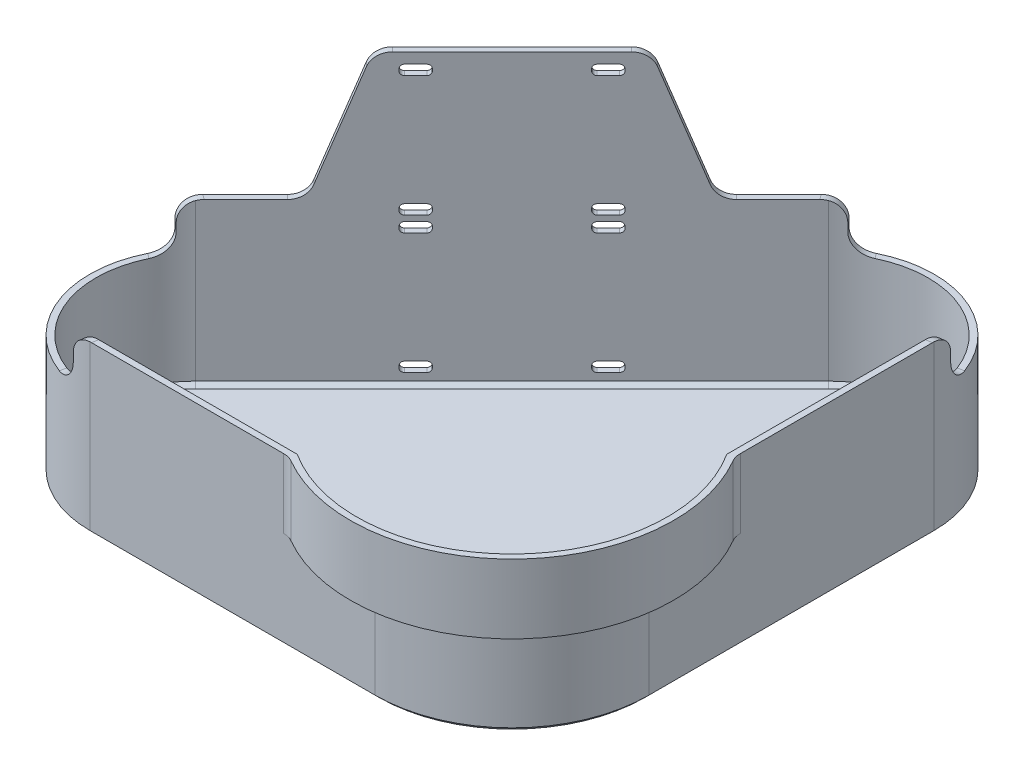
SolidWorks part; units mm, degrees
material "Nylon 101"
ref_plane "Front Plane" through (0, 0, 0) normal (0, 0, 1) x (1, 0, 0)
ref_plane "Top Plane" through (0, 0, 0) normal (0, 1, 0) x (1, 0, 0)
ref_plane "Right Plane" through (0, 0, 0) normal (1, 0, 0) x (0, 0, -1)
sketch "Module Geo" plane through (0, 0, 0) normal (0, 1, 0) x (1, 0, 0)
  line L0 (0, 0) -> (-208.4683, 0)
  line L1 (0, 208.4683) -> (-208.4683, 0)
  line L3 (0, 0) -> (0, 208.4683)
  arc A0 (-41.275, 0) -> (0, 41.275) centre (-41.275, 41.275) ccw
  arc A1 (-155.3516, 53.1166) -> (-133.35, 0) centre (-133.35, 31.115) ccw
  arc A2 (-53.1166, 155.3516) -> (0, 133.35) centre (-31.115, 133.35) cw
  circle A3 centre (-41.275, 41.275) radius 49.2125
  point P13 (0, 0)
  dimension "D1" = 31.115
  dimension "D2" = 41.275
  dimension "D4" = 98.425
  dimension "D3" = 92.075
ref_plane "Plane2" through (0, 0, 0) normal (0.7071, 0, -0.7071) x (-0.7071, 0, -0.7071)
sketch "Base Extrude" plane through (0, 0, 0) normal (0, 1, 0) x (1, 0, 0)
  line L0 (-55.5705, 30.7146) -> (-30.7146, 55.5705) construction
  line L1 (-30.7146, 55.5705) -> (-30.7146, 30.7146) construction
  line L2 (-30.7146, 30.7146) -> (-55.5705, 30.7146) construction
  line L12 (3, -3) -> (3, 215.7109)
  line L13 (3, 215.7109) -> (-215.7109, -3)
  line L14 (-215.7109, -3) -> (3, -3)
  line L15 (3, 41.275) -> (3, 133.35)
  line L16 (-55.2379, 157.4729) -> (-157.4729, 55.2379)
  line L17 (-133.35, -3) -> (-41.275, -3)
  circle A0 centre (-55.5705, 30.7146) radius 2.1526
  circle A1 centre (-30.7146, 30.7146) radius 2.1527
  circle A2 centre (-30.7146, 55.5705) radius 2.1527
  arc A14 (-157.4729, 55.2379) -> (-133.35, -3) centre (-133.35, 31.115) ccw
  arc A15 (-55.2379, 157.4729) -> (3, 133.35) centre (-31.115, 133.35) cw
  arc A16 (-41.275, -3) -> (3, 41.275) centre (-41.275, 41.275) ccw
  dimension "D2" = 4.3053
  dimension "D3" = 24.8559
  dimension "D4" = 10.5604
  dimension "D5" = 10.5604
  dimension "D1" = 3
extrude "Boss-Extrude1" add sketch "Base Extrude" along normal blind 2
sketch "Sketch3" plane through (0, 2, 0) normal (0, 1, 0) x (1, 0, 0)
  line L3 (-133.35, -3) -> (-41.275, -3)
  line L4 (3, 41.275) -> (3, 133.35)
  line L5 (-55.2379, 157.4729) -> (-157.4729, 55.2379)
  line L6 (-133.35, -3) -> (-41.275, -3)
  line L7 (3, 41.275) -> (3, 133.35)
  line L8 (-55.2379, 157.4729) -> (-157.4729, 55.2379)
  arc A3 (-157.4729, 55.2379) -> (-133.35, -3) centre (-133.35, 31.115) ccw
  arc A4 (-41.275, -3) -> (3, 41.275) centre (-41.275, 41.275) ccw
  arc A5 (3, 133.35) -> (-55.2379, 157.4729) centre (-31.115, 133.35) ccw
  arc A6 (-157.4729, 55.2379) -> (-133.35, -3) centre (-133.35, 31.115) ccw
  arc A7 (-41.275, -3) -> (3, 41.275) centre (-41.275, 41.275) ccw
  arc A8 (3, 133.35) -> (-55.2379, 157.4729) centre (-31.115, 133.35) ccw
  dimension "D1" = 0
extrude "Extrude-Thin1" add sketch "Sketch3" along normal blind 31.75 thin thin type one direction reverse wall 2
sketch "Sketch4" plane through (0, 33.75, 0) normal (0, 1, 0) x (1, 0, 0)
  line L0 (-133.35, -3) -> (-41.275, -3) construction
  line L1 (3, 41.275) -> (3, 133.35) construction
  line L5 (-133.35, -3) -> (-41.275, -3)
  line L6 (3, 41.275) -> (3, 133.35)
  line L7 (-55.2379, 157.4729) -> (-157.4729, 55.2379)
  line L8 (-133.35, -3) -> (-41.275, -3)
  line L9 (3, 41.275) -> (3, 133.35)
  line L10 (-55.2379, 157.4729) -> (-157.4729, 55.2379)
  arc A1 (-64.9609, -3) -> (3, 64.9609) centre (-41.275, 41.275) ccw
  arc A2 (-68.9493, -3) -> (3, 68.9493) centre (-41.275, 41.275) ccw
  circle A3 centre (-41.275, 41.275) radius 49.2125 construction
  arc A7 (-157.4729, 55.2379) -> (-133.35, -3) centre (-133.35, 31.115) ccw
  arc A8 (-41.275, -3) -> (3, 41.275) centre (-41.275, 41.275) ccw
  arc A9 (3, 133.35) -> (-55.2379, 157.4729) centre (-31.115, 133.35) ccw
  arc A10 (-157.4729, 55.2379) -> (-133.35, -3) centre (-133.35, 31.115) ccw
  arc A11 (-41.275, -3) -> (3, 41.275) centre (-41.275, 41.275) ccw
  arc A12 (3, 133.35) -> (-55.2379, 157.4729) centre (-31.115, 133.35) ccw
  dimension "D1" = 2
  dimension "D2" = 1
  dimension "D3" = 0
extrude "Boss-Extrude2" add sketch "Sketch4" against normal blind 2 contours L8 A1 L9 A11 | L8 A2 L9 A1
sketch "Sketch5" plane through (0, 33.75, 0) normal (0, 1, 0) x (1, 0, 0)
  line L3 (-133.35, -3) -> (-68.9493, -3)
  line L4 (3, 68.9493) -> (3, 133.35)
  line L5 (-55.2379, 157.4729) -> (-157.4729, 55.2379)
  line L6 (-133.35, -3) -> (-68.9493, -3)
  line L7 (3, 68.9493) -> (3, 133.35)
  line L8 (-55.2379, 157.4729) -> (-157.4729, 55.2379)
  arc A3 (-157.4729, 55.2379) -> (-133.35, -3) centre (-133.35, 31.115) ccw
  arc A4 (-68.9493, -3) -> (3, 68.9493) centre (-41.275, 41.275) ccw
  arc A5 (3, 133.35) -> (-55.2379, 157.4729) centre (-31.115, 133.35) ccw
  arc A6 (-157.4729, 55.2379) -> (-133.35, -3) centre (-133.35, 31.115) ccw
  arc A7 (-68.9493, -3) -> (3, 68.9493) centre (-41.275, 41.275) ccw
  arc A8 (3, 133.35) -> (-55.2379, 157.4729) centre (-31.115, 133.35) ccw
  dimension "D1" = 0
extrude "Extrude-Thin2" add sketch "Sketch5" along normal blind 20.32 thin thin type one direction reverse wall 2
ref_plane "Plane1" through (-75.2404, 0, 75.2404) normal (-0.7071, 0, 0.7071) x (0.7071, 0, 0.7071)
sketch "Sketch6" plane through (-75.2404, 0, 75.2404) normal (-0.7071, 0, 0.7071) x (0.7071, 0, 0.7071)
  line L0 (-92.1714, 54.07) -> (-150.4093, 54.07) construction
  line L1 (-165.1964, 54.07) -> (-95.3464, 54.07)
  line L2 (-165.1964, 54.07) -> (-165.1964, 38.83)
  line L3 (-165.1964, 38.83) -> (-95.3464, 38.83)
  line L4 (-95.3464, 54.07) -> (-95.3464, 38.83)
  line L6 (-92.1714, 54.07) -> (-92.1714, 0) construction
  dimension "D1" = 15.24
  dimension "D2" = 69.85
  dimension "D3" = 3.175
wrap "Wrap1" sketch "Sketch6" wrap type deboss source sketch "Sketch6" thickness 2 face at (-155.1398, 27.035, -22.0894) parameters "D1"=2
other "SurfaceCut1"
mirror "Mirror6" about plane through (0, 0, 0) normal (0.7071, 0, -0.7071) of bodies 106
sketch "Sketch9" plane through (-106.3554, 0, -106.3554) normal (-0.7071, 0, -0.7071) x (-0.7071, 0, 0.7071)
  line L0 (46.7729, 54.07) -> (31.75, 95.345)
  line L1 (-72.2911, 54.07) -> (72.2911, 54.07) construction
  line L2 (31.75, 95.345) -> (-31.75, 95.345)
  line L3 (0, 95.345) -> (0, 54.07) construction
  line L4 (-72.2911, 0) -> (72.2911, 0) construction
  line L5 (-46.7729, 54.07) -> (-31.75, 95.345)
  line L6 (-72.2911, 54.07) -> (72.2911, 54.07)
  point P8 (0, 0)
  point P11 (-45.6173, 54.07)
  line M2 (72.2911, 54.07) -> (-72.2911, 54.07)
  dimension "D1" = 41.275
  dimension "D2" = 20
  dimension "D3" = 31.75
extrude "Boss-Extrude3" add sketch "Sketch9" against normal up to surface (2 mm away) contours L2 L3 L0 M2 | L3 L2 L5 L6
fillet "Fillet1" radius 6.35 22 edges at (-136.2694, 54.07, 2.8749) (-136.0982, 54.07, 0.8822) (-138.9968, 54.07, 1.515) (-159.7514, 54.07, -51.1043) (-159.7514, 38.83, -51.1043) (-138.9968, 38.83, 1.515) (3, 42.91, -68.9493) (0.8822, 54.07, -136.0982) (-52.2119, 54.07, -157.5635) (-51.1043, 54.07, -159.7514) (2.8749, 54.07, -136.2694) (-53.5258, 54.07, -159.0714) (1.515, 54.07, -138.9968) (-51.1043, 38.83, -159.7514) (1.515, 38.83, -138.9968) (-83.1977, 95.345, -128.099) (-128.099, 95.345, -83.1977) (-138.7218, 54.07, -72.5749) (-72.5749, 54.07, -138.7218) (-68.9493, 42.91, 3) (-159.0714, 54.07, -53.5258) (-157.5635, 54.07, -52.2119)
chamfer "Chamfer1" distance 1.27 angle 45 12 edges at (-106.3554, 0, -106.3554) (-164.8682, 0, -18.0598) (-18.0598, 0, -164.8682) (-87.3125, 0, 3) (3, 0, -87.3125) (-9.9678, 0, -9.9678) (-18.8251, 2, -163.0204) (-104.9412, 2, -104.9412) (1, 2, -87.3125) (-163.0204, 2, -18.8251) (-11.3821, 2, -11.3821) (-87.3125, 2, 1)
sketch "Sketch10" plane through (-106.3554, 0, -106.3554) normal (-0.7071, 0, -0.7071) x (-0.7071, 0, 0.7071)
  line L0 (0, 1.2845) -> (0, 95.345) construction
  line L1 (25.81, 5.6802) -> (18.19, 5.6802)
  line L2 (25.81, 5.6802) -> (25.81, 8.8552)
  line L3 (25.81, 8.8552) -> (18.19, 8.8552)
  line L4 (18.19, 5.6802) -> (18.19, 8.8552)
  line L5 (27.3037, 95.345) -> (-27.3037, 95.345) construction
  line L6 (30.7099, 26.775) -> (-30.9026, 26.775) construction
  line L7 (30.7099, 33.525) -> (30.7099, 20.025) construction
  line L8 (-30.9026, 26.059) -> (-30.9025, 33.8656) construction
  line L9 (3.8624, 43.3436) -> (3.8624, 54.2314) construction
  line L10 (-19.1311, 43.3436) -> (19.1311, 43.3436) construction
  line L12 (3.8624, 48.7875) -> (29.7734, 48.7875) construction
  line L13 (22, 8.8552) -> (22, 10.1252) construction
  line L14 (19.2666, 10.1252) -> (24.7334, 10.1252) construction
  line L15 (-25.81, 8.8552) -> (-18.19, 8.8552)
  line L16 (-18.19, 5.6802) -> (-18.19, 8.8552)
  line L17 (-25.81, 5.6802) -> (-18.19, 5.6802)
  line L18 (-25.81, 5.6802) -> (-25.81, 8.8552)
  line L19 (-25.81, 47.8698) -> (-25.81, 44.6948)
  line L20 (-25.81, 47.8698) -> (-18.19, 47.8698)
  line L21 (-18.19, 47.8698) -> (-18.19, 44.6948)
  line L22 (-25.81, 44.6948) -> (-18.19, 44.6948)
  line L23 (25.81, 44.6948) -> (18.19, 44.6948)
  line L24 (18.19, 47.8698) -> (18.19, 44.6948)
  line L25 (25.81, 47.8698) -> (18.19, 47.8698)
  line L26 (25.81, 47.8698) -> (25.81, 44.6948)
  line L27 (25.81, 49.7052) -> (25.81, 52.8802)
  line L28 (25.81, 49.7052) -> (18.19, 49.7052)
  line L29 (18.19, 49.7052) -> (18.19, 52.8802)
  line L30 (25.81, 52.8802) -> (18.19, 52.8802)
  line L31 (-25.81, 49.7052) -> (-18.19, 49.7052)
  line L32 (-18.19, 49.7052) -> (-18.19, 52.8802)
  line L33 (-25.81, 52.8802) -> (-18.19, 52.8802)
  line L34 (-25.81, 49.7052) -> (-25.81, 52.8802)
  line L35 (-25.81, 91.8948) -> (-25.81, 88.7198)
  line L36 (-25.81, 91.8948) -> (-18.19, 91.8948)
  line L37 (-18.19, 91.8948) -> (-18.19, 88.7198)
  line L38 (-25.81, 88.7198) -> (-18.19, 88.7198)
  line L39 (25.81, 88.7198) -> (18.19, 88.7198)
  line L40 (18.19, 91.8948) -> (18.19, 88.7198)
  line L41 (25.81, 91.8948) -> (18.19, 91.8948)
  line L42 (25.81, 91.8948) -> (25.81, 88.7198)
  line L43 (19.1311, 54.2314) -> (-19.1311, 54.2314) construction
  point P19 (3.8624, 54.2314)
  point P58 (21.5496, 9.3315)
  point P59 (16.7625, 12.8429)
  dimension "D1" = 3.175
  dimension "D2" = 7.62
  dimension "D3" = 1.27
extrude "Cut-Extrude2" cut sketch "Sketch10" against normal up to next
fillet "Fillet2" radius 1.27 32 edges at (-123.8988, 5.6802, -87.3979) (-118.5106, 5.6802, -92.7861) (-118.5106, 8.8552, -92.7861) (-123.8988, 88.7198, -87.3979) (-118.5106, 88.7198, -92.7861) (-118.5106, 91.8948, -92.7861) (-123.8988, 91.8948, -87.3979) (-92.7861, 91.8948, -118.5106) (-92.7861, 88.7198, -118.5106) (-87.3979, 88.7198, -123.8988) (-87.3979, 91.8948, -123.8988) (-87.3979, 52.8802, -123.8988) (-92.7861, 52.8802, -118.5106) (-92.7861, 49.7052, -118.5106) (-87.3979, 49.7052, -123.8988) (-118.5106, 49.7052, -92.7861) (-118.5106, 52.8802, -92.7861) (-123.8988, 52.8802, -87.3979) (-123.8988, 49.7052, -87.3979) (-123.8988, 44.6948, -87.3979) (-118.5106, 44.6948, -92.7861) (-118.5106, 47.8698, -92.7861) (-123.8988, 47.8698, -87.3979) (-92.7861, 47.8698, -118.5106) (-92.7861, 44.6948, -118.5106) (-87.3979, 44.6948, -123.8988) (-87.3979, 47.8698, -123.8988) (-87.3979, 5.6802, -123.8988) (-87.3979, 8.8552, -123.8988) (-92.7861, 8.8552, -118.5106) (-92.7861, 5.6802, -118.5106) (-123.8988, 8.8552, -87.3979)
equation "\"D1@Base Extrude\"=3mm"
equation "\"D1@Boss-Extrude1\"=2mm"
equation "\"D1@Extrude-Thin1\"=2mm"
equation "\"D5@Extrude-Thin1\"=2mm"
equation "\"D1@Sketch4\"=2mm"
equation "\"D2@Sketch4\"=1mm"
equation "\"D1@Boss-Extrude2\"=2mm"
equation "\"D5@Extrude-Thin2\"=2mm"
